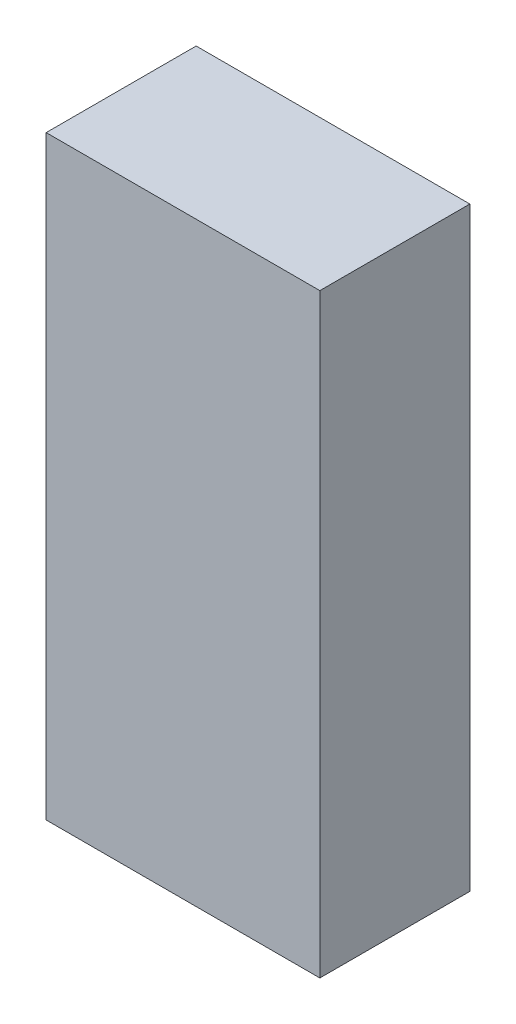
SolidWorks part; units mm, degrees
ref_plane "Front Plane" through (0, 0, 0) normal (0, 0, 1) x (1, 0, 0)
ref_plane "Top Plane" through (0, 0, 0) normal (0, 1, 0) x (1, 0, 0)
ref_plane "Right Plane" through (0, 0, 0) normal (1, 0, 0) x (0, 0, -1)
sketch "Sketch1" plane through (0, 0, 0) normal (0, 1, 0) x (1, 0, 0)
  line L1 (-8.85, -4.85) -> (8.85, -4.85)
  line L2 (-8.85, -4.85) -> (-8.85, 4.85)
  line L3 (-8.85, 4.85) -> (8.85, 4.85)
  line L4 (8.85, -4.85) -> (8.85, 4.85)
  line L5 (-8.85, -4.85) -> (8.85, 4.85) construction
  line L6 (-8.85, 4.85) -> (8.85, -4.85) construction
  point P0 (0, 0)
  dimension "D1" = 17.7
  dimension "D2" = 9.7
extrude "Boss-Extrude1" add sketch "Sketch1" along normal blind 38.5
